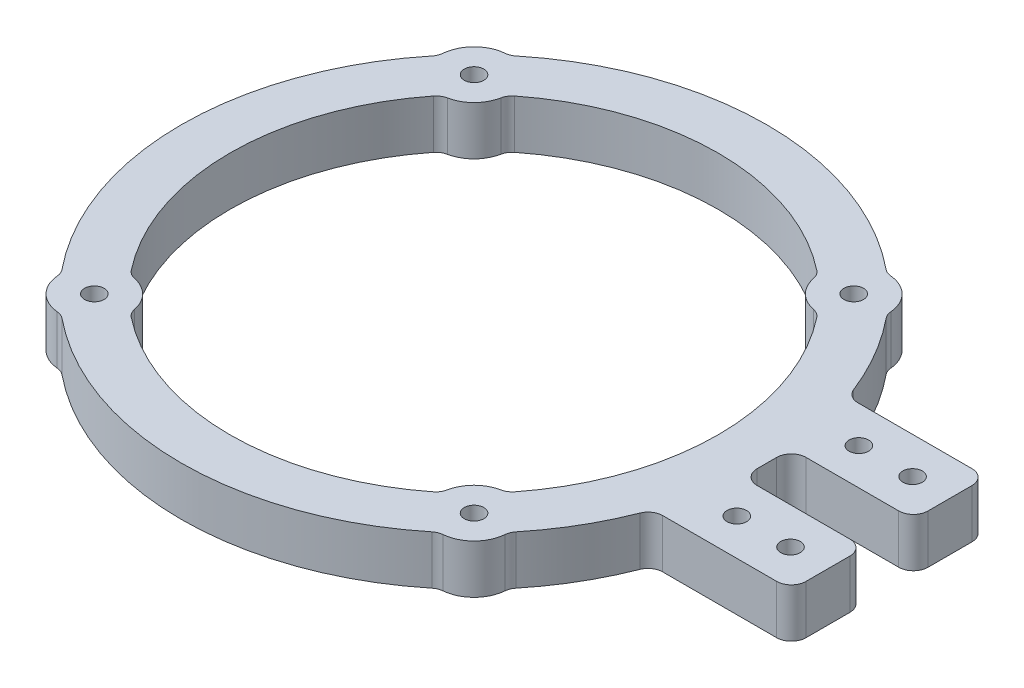
SolidWorks part; units mm, degrees
material "1060 Alloy"
ref_plane "Front Plane" through (0, 0, 0) normal (0, 0, 1) x (1, 0, 0)
ref_plane "Top Plane" through (0, 0, 0) normal (0, 1, 0) x (1, 0, 0)
ref_plane "Right Plane" through (0, 0, 0) normal (1, 0, 0) x (0, 0, -1)
sketch "Sketch1" plane through (0, 0, 0) normal (0, 1, 0) x (1, 0, 0)
  line L0 (0, -50) -> (0, -60) construction
  line L1 (0, 0) -> (0, -50) construction
  line L2 (56.5685, -20) -> (85, -20)
  line L3 (85, -20) -> (85, -5)
  line L4 (85, -5) -> (60, -5)
  line L5 (60, -5) -> (60, 5)
  line L6 (60, 5) -> (85, 5)
  line L7 (85, 5) -> (85, 20)
  line L8 (85, 20) -> (56.5685, 20)
  circle A0 centre (0, 0) radius 50
  circle A1 centre (0, 0) radius 60 construction
  arc A2 (56.5685, 20) -> (56.5685, -20) centre (0, 0) ccw
  dimension "D1" = 100
  dimension "D5" = 60
  dimension "D2" = 10
  dimension "D3" = 10
  dimension "D4" = 15
  dimension "D6" = 25
extrude "Boss-Extrude1" add sketch "Sketch1" along normal blind 10
sketch "Sketch3" plane through (0, 10, 0) normal (0, 1, 0) x (1, 0, 0)
  line L0 (38.8909, 38.8909) -> (38.8909, -38.8909) construction
  line L1 (60, -5) -> (60, 5) construction
  circle A0 centre (0, 0) radius 55 construction
  circle A1 centre (38.8909, -38.8909) radius 7
  circle A2 centre (-38.8909, -38.8909) radius 7
  circle A3 centre (-38.8909, 38.8909) radius 7
  circle A4 centre (38.8909, 38.8909) radius 7
  point P14 (0, 0)
  dimension "D1" = 110
  dimension "D2" = 14
  dimension "D3" = 4
extrude "Boss-Extrude2" add sketch "Sketch3" against normal up to surface (10 mm away) up to face at (57.0711, 0, 0)
sketch "Sketch4" plane through (0, 10, 0) normal (0, 1, 0) x (1, 0, 0)
  circle A0 centre (38.8909, -38.8909) radius 2
  circle A1 centre (-38.8909, -38.8909) radius 2
  circle A2 centre (-38.8909, 38.8909) radius 2
  circle A3 centre (38.8909, 38.8909) radius 2
  point P12 (0, 0)
  dimension "D1" = 4
  dimension "D2" = 4
extrude "Cut-Extrude1" cut sketch "Sketch4" against normal blind 10
fillet "Fillet1" radius 3 24 edges at (85, 5, -20) (85, 5, -5) (85, 5, 5) (85, 5, 20) (31.9018, 5, 38.5003) (38.5003, 5, 31.9018) (38.5003, 5, -31.9018) (31.9018, 5, -38.5003) (-31.9018, 5, -38.5003) (-38.5003, 5, -31.9018) (-38.6573, 5, -45.887) (-45.887, 5, -38.6573) (45.887, 5, -38.6573) (38.6573, 5, -45.887) (-38.5003, 5, 31.9018) (-31.9018, 5, 38.5003) (-45.887, 5, 38.6573) (-38.6573, 5, 45.887) (38.6573, 5, 45.887) (45.887, 5, 38.6573) (56.5685, 5, 20) (56.5685, 5, -20) (60, 5, 5) (60, 5, -5)
sketch "Sketch5" plane through (0, 10, 0) normal (0, 1, 0) x (1, 0, 0)
  line L0 (58.6515, 20) -> (85, 5) construction
  line L1 (85, 20) -> (58.6515, 5) construction
  line L2 (58.6515, 5) -> (85, 5) construction
  line L3 (58.6515, 20) -> (58.6515, 5) construction
  line L4 (66.3258, 12.5) -> (77.3258, 12.5) construction
  line L5 (58.6515, 20) -> (85, 20) construction
  line L6 (85, 20) -> (85, 5) construction
  line L7 (63, 5) -> (82, 5) construction
  line L8 (85, 8) -> (85, 17) construction
  line L9 (58.6515, -5) -> (85, -20) construction
  line L10 (85, -5) -> (58.6515, -20) construction
  line L11 (58.6515, -20) -> (85, -20) construction
  line L12 (58.6515, -5) -> (58.6515, -20) construction
  line L13 (66.3258, -12.5) -> (77.3258, -12.5) construction
  line L14 (58.6515, -5) -> (85, -5) construction
  line L15 (85, -5) -> (85, -20) construction
  line L16 (82, -5) -> (63, -5) construction
  line L17 (58.6515, -20) -> (82, -20) construction
  circle A0 centre (66.3258, 12.5) radius 2
  circle A1 centre (77.3258, 12.5) radius 2
  circle A2 centre (66.3258, -12.5) radius 2
  circle A3 centre (77.3258, -12.5) radius 2
  point P11 (71.8258, 12.5)
  point P21 (71.8258, -12.5)
  dimension "D2" = 4
  dimension "D3" = 4
  dimension "D5" = 4
  dimension "D6" = 4
  dimension "D1" = 11
  dimension "D4" = 11
extrude "Cut-Extrude2" cut sketch "Sketch5" against normal blind 10
